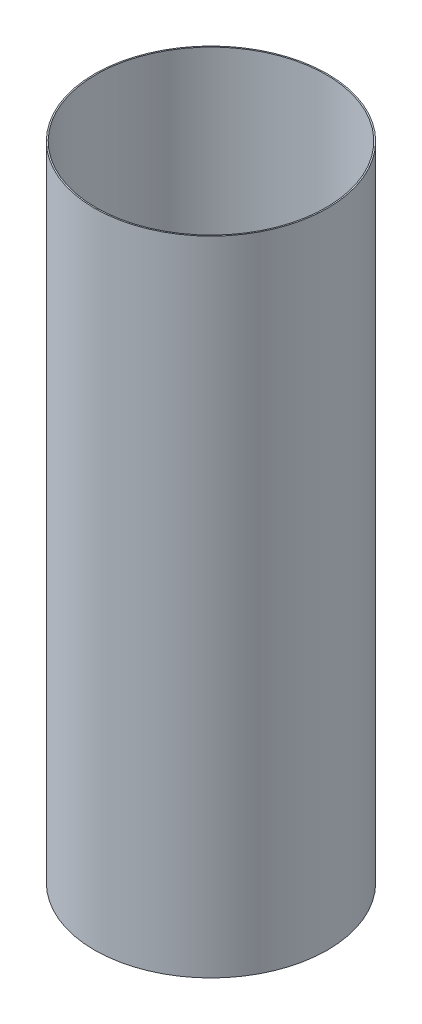
SolidWorks part; units mm, degrees
material "Galvanized Steel"
ref_plane "Front Plane" through (0, 0, 0) normal (0, 0, 1) x (1, 0, 0)
ref_plane "Top Plane" through (0, 0, 0) normal (0, 1, 0) x (1, 0, 0)
ref_plane "Right Plane" through (0, 0, 0) normal (1, 0, 0) x (0, 0, -1)
sketch "Sketch1" plane through (0, 0, 0) normal (0, 1, 0) x (1, 0, 0)
  circle A0 centre (0, 0) radius 73.66
  circle A1 centre (0, 0) radius 72.8472
  dimension "D1" = 147.32
  dimension "D2" = 0.8128
extrude "Boss-Extrude1" add sketch "Sketch1" along normal blind 406.4
